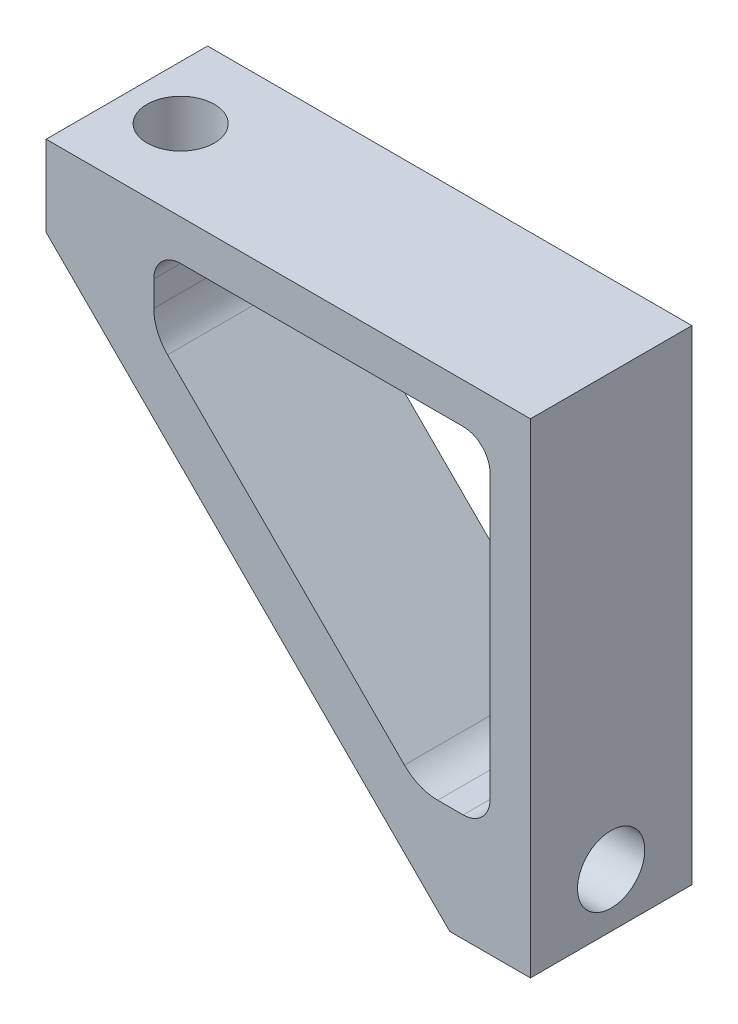
SolidWorks part; units mm, degrees
material "6061 合金"
ref_plane "前视基准面" through (0, 0, 0) normal (0, 0, 1) x (1, 0, 0)
ref_plane "上视基准面" through (0, 0, 0) normal (0, 1, 0) x (1, 0, 0)
ref_plane "右视基准面" through (0, 0, 0) normal (1, 0, 0) x (0, 0, -1)
sketch "草图1" plane through (0, 0, 0) normal (0, 0, 1) x (1, 0, 0)
  line L0 (-18, 0) -> (0, 0)
  line L1 (0, 0) -> (0, -18)
  line L6 (-18, 0) -> (-18, -3)
  line L7 (-18, -3) -> (-3, -18)
  line L8 (-3, -18) -> (0, -18)
  dimension "D1" = 3
  dimension "D3" = 18
extrude "凸台-拉伸1" add sketch "草图1" along normal blind 6
sketch "草图2" plane through (0, 0, 6) normal (0, 0, 1) x (1, 0, 0)
  line L5 (-14, -1.5) -> (-14, -4.1716)
  line L6 (-14, -4.1716) -> (-4.1716, -14)
  line L7 (-4.1716, -14) -> (-1.5, -14)
  line L8 (-1.5, -14) -> (-1.5, -1.5)
  line L9 (-1.5, -1.5) -> (-14, -1.5)
  line L10 (-18, -3) -> (-3, -18) construction
  line L11 (0, 0) -> (-18, 0) construction
  line L12 (0, -18) -> (0, 0) construction
  line L13 (-18, 0) -> (-18, -3) construction
  dimension "D1" = 1.5
  dimension "D2" = 1.5
  dimension "D3" = 4
  dimension "D4" = 2
extrude "切除-拉伸1" cut sketch "草图2" against normal through all
sketch "草图3" plane through (0, 0, 0) normal (1, 0, 0) x (0, 0, -1)
  line L0 (-3, 0) -> (-3, -18) construction
  line L1 (-6, 0) -> (0, 0) construction
  line L2 (-6, -18) -> (0, -18) construction
  circle A0 centre (-3, -16) radius 1.25
  dimension "D1" = 2.5
  dimension "D2" = 2
extrude "切除-拉伸2" cut sketch "草图3" against normal through all
ref_plane "基准面1" through (0, 0, 0) normal (-0.7071, 0.7071, 0) x (0, 0, 1)
mirror "镜向1" about plane through (0, 0, 0) normal (-0.7071, 0.7071, 0) of "切除-拉伸2"
fillet "圆角1" radius 1 3 edges at (-1.5, -1.5, 3) (-1.5, -14, 3) (-14, -1.5, 3)
fillet "圆角2" radius 1.75 2 edges at (-4.1716, -14, 3) (-14, -4.1716, 3)
